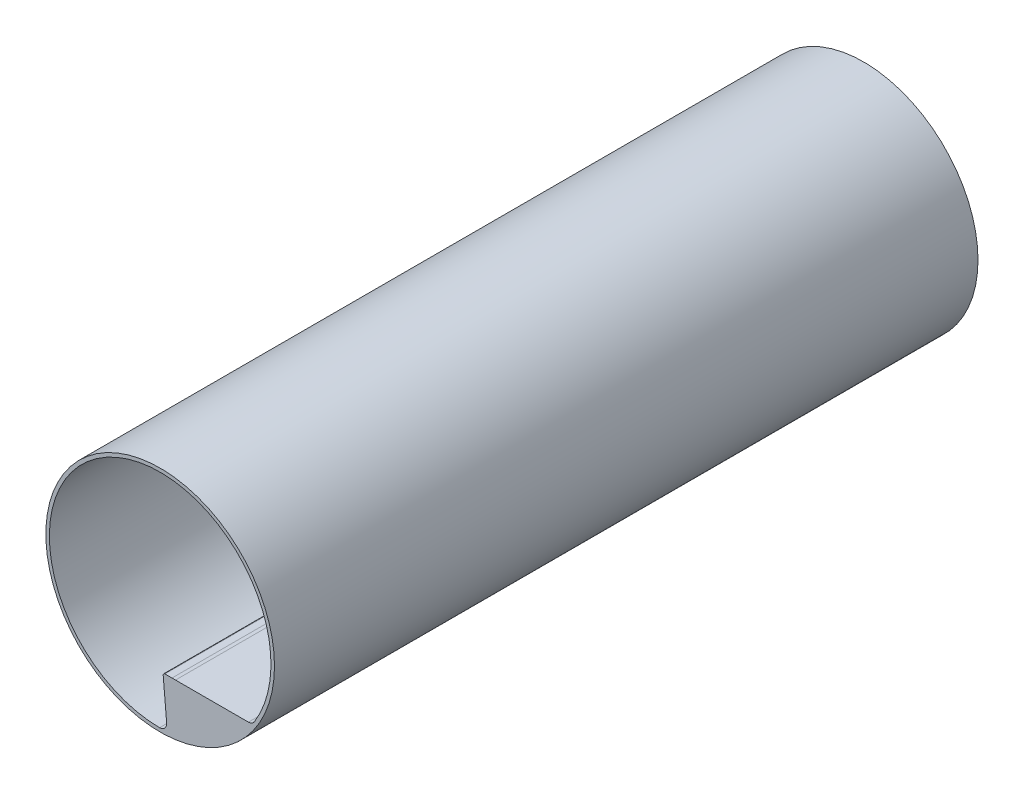
SolidWorks part; units mm, degrees
ref_plane "Front Plane" through (0, 0, 0) normal (0, 0, 1) x (1, 0, 0)
ref_plane "Top Plane" through (0, 0, 0) normal (0, 1, 0) x (1, 0, 0)
ref_plane "Right Plane" through (0, 0, 0) normal (1, 0, 0) x (0, 0, -1)
sketch "Sketch2" plane through (0, 0, 0) normal (0, 0, 1) x (1, 0, 0)
  line L0 (0, 3250) -> (0, -3250) construction
  line L1 (-3150, 0) -> (3150, 0) construction
  line L2 (80.8398, -1750) -> (2619.1602, -1750)
  line L3 (80.8398, -1750) -> (202.7525, -3143.4681)
  line L4 (80.8398, -1750) -> (-2619.1602, -1750) construction
  circle A0 centre (0, 0) radius 3250
  arc A1 (2619.1602, -1750) -> (202.7525, -3143.4681) centre (0, 0) ccw
  point P16 (0, -1750)
  dimension "D1" = 6500
  dimension "D2" = 100
  dimension "D3" = 85
  dimension "D5" = 1500
  dimension "D6" = 2700
extrude "Boss-Extrude1" add sketch "Sketch2" along normal blind 20000
fillet "Fillet1" radius 200 2 edges at (202.7525, -3143.4681, 10000) (2619.1602, -1750, 10000)
fillet "Fillet2" radius 50 1 edges at (80.8398, -1750, 10000)
sketch "Sketch3" plane through (0, -1750, 0) normal (0, 1, 0) x (1, 0, 0)
  line L0 (135.4053, -20000) -> (2509.9801, -20000) construction
  line L1 (436.7242, -20000) -> (336.7242, -20000)
  line L2 (436.7242, -20000) -> (436.7242, 0)
  line L3 (436.7242, 0) -> (336.7242, 0)
  line L4 (336.7242, -20000) -> (336.7242, 0)
  line L5 (135.4053, 0) -> (2509.9801, 0) construction
  dimension "D1" = 100
  dimension "D2" = 201.3189
split line "Split Line1"
equation "\"LineWidth\"=0.1"
equation "\"D1@Sketch3\"=\"LineWidth\""
